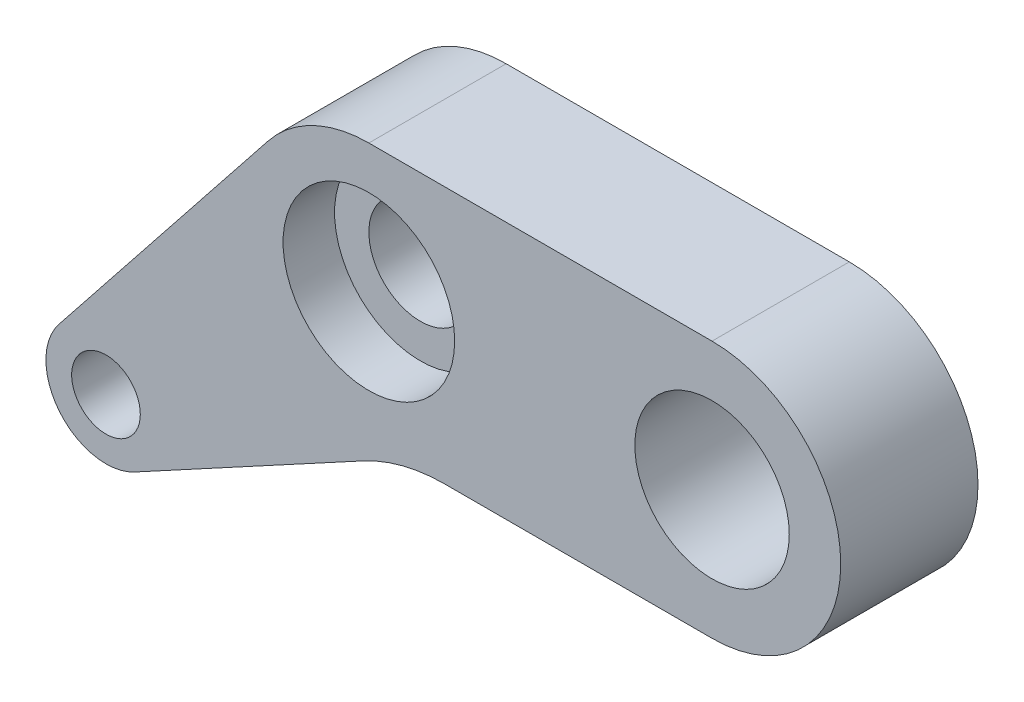
SolidWorks part; units mm, degrees
ref_plane "Спереди" through (0, 0, 0) normal (0, 0, 1) x (1, 0, 0)
ref_plane "Сверху" through (0, 0, 0) normal (0, 1, 0) x (1, 0, 0)
ref_plane "Справа" through (0, 0, 0) normal (1, 0, 0) x (0, 0, -1)
sketch "Эскиз1" plane through (0, 0, 0) normal (0, 0, 1) x (1, 0, 0)
  line L0 (0, 0) -> (-20, 0) construction
  line L1 (-20, 0) -> (-35.3209, -12.8558) construction
  line L2 (0, 7.5) -> (-20, 7.5)
  line L3 (0, -7.5) -> (-20, -7.5)
  line L4 (-38.0614, -10.6787) -> (-25.8726, 4.6651)
  line L5 (-33.6528, -15.9327) -> (-16.4256, -6.5934)
  circle A0 centre (0, 0) radius 7.5
  circle A1 centre (-35.3209, -12.8558) radius 3.5
  circle A2 centre (-20, 0) radius 7.5
  circle A3 centre (0, 0) radius 4.5
  circle A4 centre (-20, 0) radius 3
  circle A5 centre (-35.3209, -12.8558) radius 2
  dimension "D1" = 15
  dimension "D5" = 7
  dimension "D6" = 9
  dimension "D7" = 6
  dimension "D8" = 4
  dimension "D2" = 140
  dimension "D3" = 20
  dimension "D4" = 20
extrude "Бобышка-Вытянуть1" add sketch "Эскиз1" along normal blind 8 contours A1 A5 | A2 L4 A1 L5 L3 | A2 A4 | A2 L3 L5 | A2 L5 L3 A0 L2 | A0 A3
fillet "Скругление1" radius 10 1 edges at (-18.0978, -7.5, 4)
sketch "Эскиз2" plane through (0, 0, 8) normal (0, 0, 1) x (1, 0, 0)
  circle A0 centre (-20, 0) radius 5
  dimension "D1" = 10
extrude "Вырез-Вытянуть1" cut sketch "Эскиз2" against normal blind 3
